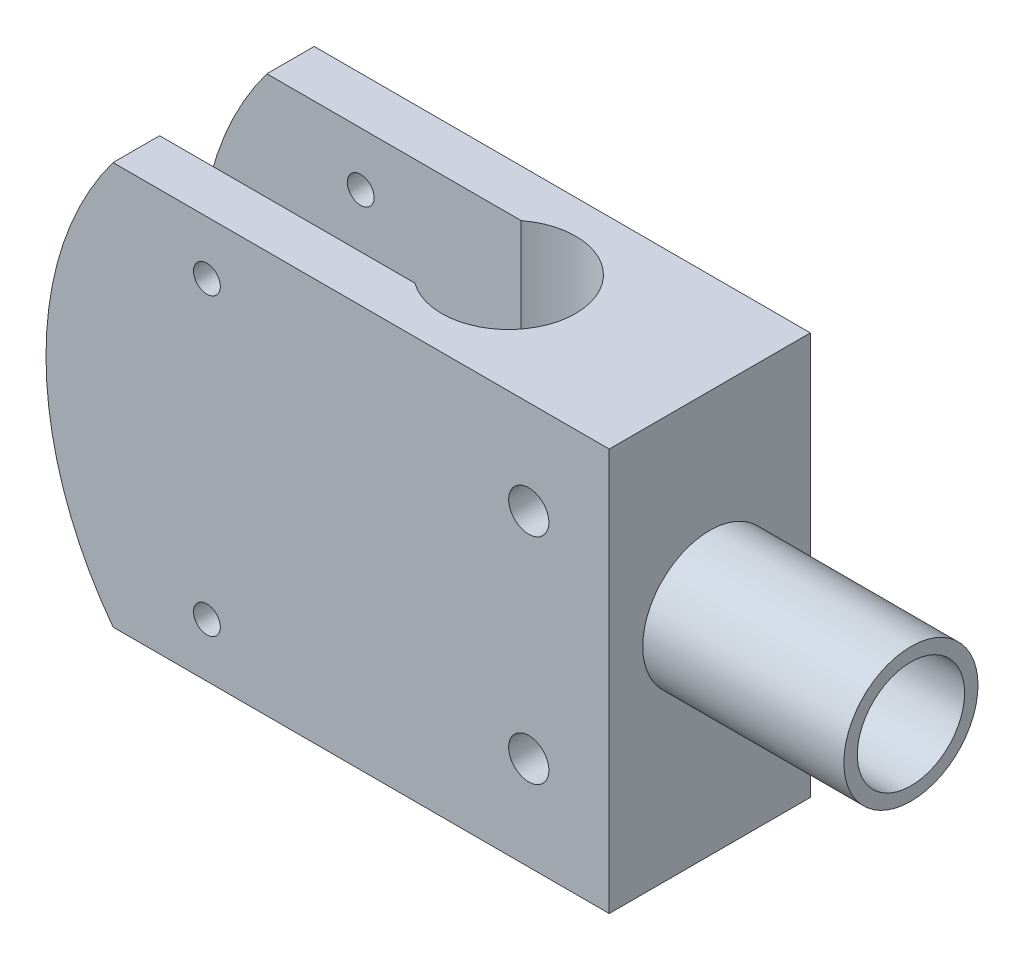
SolidWorks part; units mm, degrees
material "6063-O"
ref_plane "Front" through (0, 0, 0) normal (0, 0, 1) x (1, 0, 0)
ref_plane "Top" through (0, 0, 0) normal (0, 1, 0) x (1, 0, 0)
ref_plane "Right" through (0, 0, 0) normal (1, 0, 0) x (0, 0, -1)
sketch "Sketch1" plane through (0, 0, 0) normal (0, 0, 1) x (1, 0, 0)
  line L1 (0, 0) -> (42, 0)
  line L2 (0, 0) -> (0, 30)
  line L3 (0, 30) -> (42, 30)
  line L4 (42, 0) -> (42, 30)
  dimension "D1" = 30
  dimension "D2" = 42
extrude "Boss-Extrude1" add sketch "Sketch1" along normal blind 15
sketch "Sketch3" plane through (0, 0, 15) normal (0, 0, 1) x (1, 0, 0)
  line L0 (42, 0) -> (42, 30) construction
  line L1 (0, 0) -> (42, 0) construction
  circle A0 centre (36, 23) radius 1.5
  circle A1 centre (36, 7) radius 1.5
  dimension "D1" = 3
  dimension "D2" = 3
  dimension "D3" = 6
  dimension "D4" = 6
  dimension "D5" = 16
  dimension "D6" = 7
extrude "Cut-Extrude1" cut sketch "Sketch3" against normal blind 15
sketch "Sketch4" plane through (42, 0, 0) normal (1, 0, 0) x (0, 0, -1)
  line L0 (-15, 0) -> (0, 0) construction
  line L1 (0, 0) -> (0, 30) construction
  circle A0 centre (-7.5, 16) radius 5
  circle A1 centre (-7.5, 16) radius 4
  dimension "D1" = 10
  dimension "D2" = 16
  dimension "D3" = 7.5
  dimension "D4" = 8
extrude "Boss-Extrude2" add sketch "Sketch4" along normal blind 15
sketch "Sketch5" plane through (0, 0, 0) normal (0, -1, 0) x (1, 0, 0)
  line L0 (42, 15) -> (42, 0) construction
  line L2 (24.0413, 11.5307) -> (0, 11.5307)
  line L3 (0, 15) -> (0, 0) construction
  line L4 (0, 11.5307) -> (0, 3.5307)
  line L5 (0, 3.5307) -> (23.9595, 3.5307)
  arc A0 (23.9595, 3.5307) -> (24.0413, 11.5307) centre (27, 7.5) ccw
  dimension "D1" = 10
  dimension "D2" = 15
  dimension "D3" = 8
extrude "Cut-Extrude2" cut sketch "Sketch5" against normal blind 30
sketch "Sketch6" plane through (0, 0, 15) normal (0, 0, 1) x (1, 0, 0)
  line L0 (0, 0) -> (42, 0) construction
  line L1 (42, 30) -> (0, 30) construction
  line L2 (0, 30) -> (0, 0) construction
  line L3 (5, 30) -> (0, 30)
  line L4 (0, 30) -> (0, 0)
  line L5 (0, 0) -> (5, 0)
  arc A0 (5, 0) -> (5, 30) centre (25, 15) cw
  point P3 (0, 15)
  line M3 (0, 30) -> (0, 0)
  line M4 (0, 0) -> (42, 0)
  line M6 (42, 30) -> (0, 30)
  dimension "D1" = 5
  dimension "D2" = 5
  dimension "D3" = 0
extrude "Cut-Extrude3" cut sketch "Sketch6" against normal blind 30 contours A0 M3 M6 | A0 L4 M4
sketch "Sketch7" plane through (0, 0, 15) normal (0, 0, 1) x (1, 0, 0)
  line L0 (5, 0) -> (42, 0) construction
  line L1 (42, 0) -> (42, 30) construction
  circle A0 centre (12, 26) radius 1
  circle A1 centre (12, 4) radius 1
  dimension "D1" = 2
  dimension "D2" = 2
  dimension "D3" = 22
  dimension "D4" = 4
  dimension "D5" = 30
extrude "Cut-Extrude4" cut sketch "Sketch7" against normal blind 30
